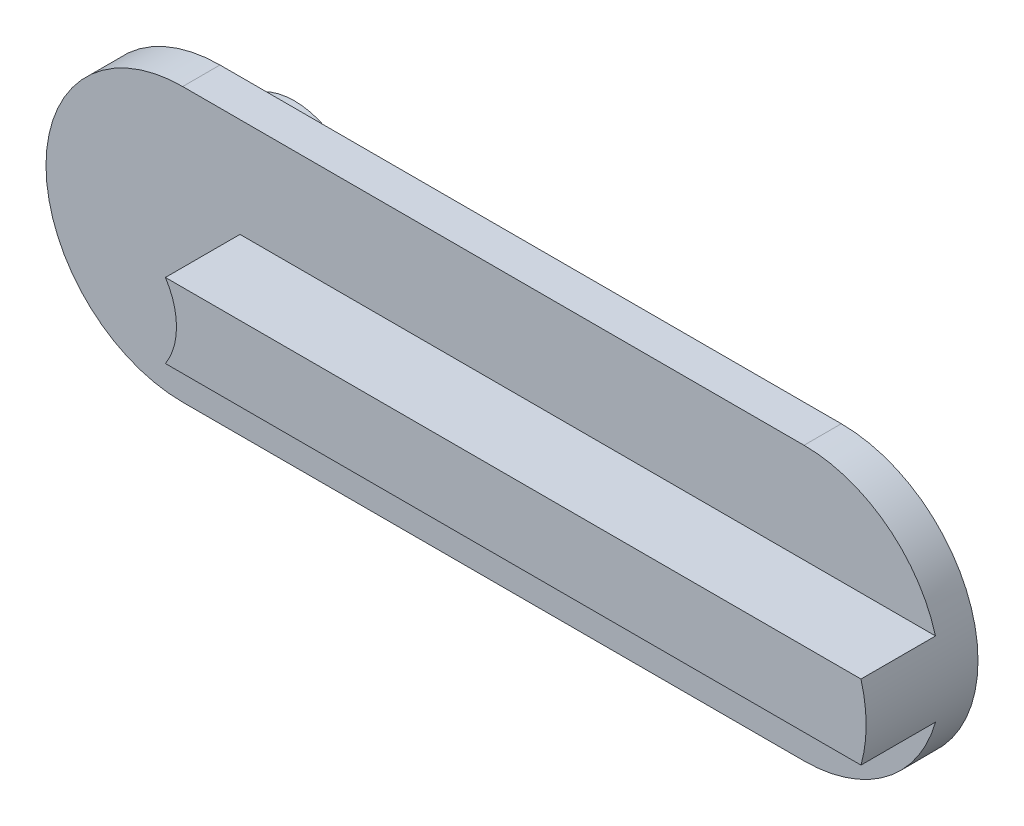
SolidWorks part; units mm, degrees
ref_plane "Front Plane" through (0, 0, 0) normal (0, 0, 1) x (1, 0, 0)
ref_plane "Top Plane" through (0, 0, 0) normal (0, 1, 0) x (1, 0, 0)
ref_plane "Right Plane" through (0, 0, 0) normal (1, 0, 0) x (0, 0, -1)
sketch "Sketch2" plane through (0, 0, 0) normal (0, 0, 1) x (1, 0, 0)
  line L0 (-50, 0) -> (50, 0) construction
  line L1 (-50, 22) -> (50, 22)
  line L2 (-50, -22) -> (50, -22)
  line L4 (50, 0) -> (72, 0) construction
  arc A0 (-50, 22) -> (-50, -22) centre (-50, 0) ccw
  arc A1 (50, -22) -> (50, 22) centre (50, 0) ccw
  point P2 (0, 0)
  dimension "D2" = 22
  dimension "D1" = 100
extrude "Boss-Extrude4" add sketch "Sketch2" along normal blind 6
sketch "Sketch5" plane through (0, 0, 6) normal (0, 0, 1) x (1, 0, 0)
  line L0 (-39, 0) -> (72, 0) construction
  line L1 (-40.7805, 6) -> (71.166, 6)
  line L2 (-40.7805, -6) -> (71.166, -6)
  arc A0 (-40.7805, -6) -> (-40.7805, 6) centre (-50, 0) ccw
  arc A1 (71.166, -6) -> (71.166, 6) centre (50, 0) ccw
  dimension "D1" = 22
  dimension "D2" = 6
extrude "Boss-Extrude6" add sketch "Sketch5" along normal blind 12
sketch "Sketch7" plane through (0, 0, 0) normal (0, 0, -1) x (-1, 0, 0)
  circle A0 centre (50, 0) radius 11
  dimension "D1" = 22
extrude "Boss-Extrude7" add sketch "Sketch7" along normal blind 12
